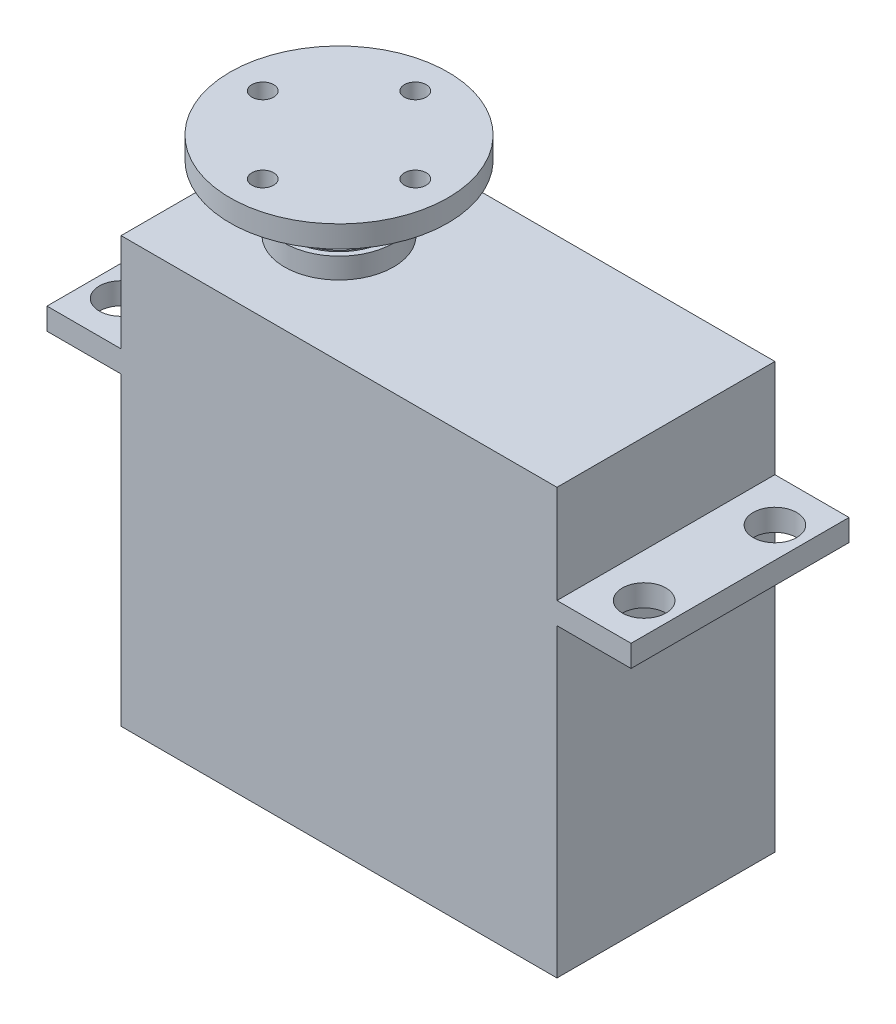
SolidWorks part; units mm, degrees
ref_plane "Front Plane" through (0, 0, 0) normal (0, 0, 1) x (1, 0, 0)
ref_plane "Top Plane" through (0, 0, 0) normal (0, 1, 0) x (1, 0, 0)
ref_plane "Right Plane" through (0, 0, 0) normal (1, 0, 0) x (0, 0, -1)
sketch "Sketch1" plane through (0, 0, 0) normal (0, 0, 1) x (1, 0, 0)
  line L0 (0, -55) -> (0, 55) construction
  line L1 (-20, 17.723) -> (20, 17.723)
  line L2 (-20, 17.723) -> (-20, -21.277)
  line L3 (-20, -21.277) -> (20, -21.277)
  line L4 (20, 17.723) -> (20, -21.277)
  line L5 (20, 8.723) -> (26.8, 8.723)
  line L6 (20, 8.723) -> (20, 6.723)
  line L7 (20, 6.723) -> (26.8, 6.723)
  line L8 (26.8, 8.723) -> (26.8, 6.723)
  line L9 (-26.8, 8.723) -> (-26.8, 6.723)
  line L10 (-20, 6.723) -> (-26.8, 6.723)
  line L11 (-20, 17.723) -> (-20, -21.277)
  line L12 (-20, 8.723) -> (-26.8, 8.723)
  dimension "D1" = 39
  dimension "D2" = 40
  dimension "D3" = 28
  dimension "D4" = 2
  dimension "D5" = 6.8
extrude "Boss-Extrude1" add sketch "Sketch1" along normal blind 20 contours L11 L12 L9 L10 | L4 L1 L2 L11 L3 | L8 L5 L4 L7
sketch "Sketch2" plane through (0, 17.723, 0) normal (0, 1, 0) x (1, 0, 0)
  circle A0 centre (-10, -10) radius 10
  circle A1 centre (-10, -10) radius 5
  circle A2 centre (-10, -10) radius 4.5
  dimension "D2" = 20
  dimension "D1" = 10
  dimension "D3" = 10
extrude "Boss-Extrude2" add sketch "Sketch2" along normal blind 2 contours A2
sketch "Sketch3" plane through (0, 17.723, 0) normal (0, 1, 0) x (1, 0, 0)
  circle A0 centre (-10, -10) radius 5
extrude "Boss-Extrude3" add sketch "Sketch3" along normal blind 1.9
sketch "Sketch4" plane through (0, 19.723, 0) normal (0, 1, 0) x (1, 0, 0)
  circle A0 centre (-10, -10) radius 3
  dimension "D1" = 10
  dimension "D2" = 10
extrude "Boss-Extrude4" add sketch "Sketch4" along normal blind 4
sketch "Sketch5" plane through (0, 23.723, 0) normal (0, 1, 0) x (1, 0, 0)
  circle A0 centre (-10, -10) radius 10
  dimension "D1" = 20
  dimension "D2" = 10
  dimension "D3" = 10
extrude "Boss-Extrude5" add sketch "Sketch5" along normal blind 2
sketch "Sketch6" plane through (0, 8.723, 0) normal (0, 1, 0) x (1, 0, 0)
  line L0 (20, -20) -> (20, 0) construction
  circle A0 centre (24, -4) radius 2
  circle A1 centre (24, -16) radius 2
  dimension "D1" = 4
  dimension "D2" = 4
  dimension "D3" = 4
  dimension "D4" = 4
  dimension "D5" = 4
  dimension "D6" = 4
extrude "Cut-Extrude1" cut sketch "Sketch6" against normal blind 10
sketch "Sketch7" plane through (0, 8.723, 0) normal (0, 1, 0) x (1, 0, 0)
  circle A0 centre (-24, -4) radius 2
  circle A1 centre (-24, -16) radius 2
  dimension "D5" = 4
  dimension "D6" = 4
  dimension "D1" = 4
  dimension "D2" = 4
  dimension "D3" = 4
  dimension "D4" = 4
extrude "Cut-Extrude2" cut sketch "Sketch7" against normal blind 10
sketch "Sketch8" plane through (0, 25.723, 0) normal (0, 1, 0) x (1, 0, 0)
  line L0 (-10, -10) -> (-10, -20)
  line L1 (-10, -20) -> (-10, 0)
  line L2 (-10, -10) -> (0, -10)
  line L3 (0, -10) -> (-20, -10)
  circle A0 centre (-10, -3) radius 1
  circle A1 centre (-3, -10) radius 1
  circle A2 centre (-17, -10) radius 1
  circle A3 centre (-10, -17) radius 1
  circle A4 centre (-10, -10) radius 1.7012
  circle A7 centre (-10, -10) radius 10 construction
  dimension "D1" = 2
  dimension "D2" = 2
  dimension "D3" = 2
  dimension "D4" = 2
  dimension "D5" = 14
  dimension "D6" = 14
  dimension "D7" = 10
  dimension "D8" = 10
  dimension "D9" = 7
  dimension "D10" = 7
  dimension "D11" = 0
  dimension "D12" = 0
  dimension "D13" = 0
extrude "Cut-Extrude3" cut sketch "Sketch8" against normal blind 5 contours L3 A2 | L3 A2 | L1 A0 | L1 A0 | L3 A1 | L1 A3 | L1 A3
